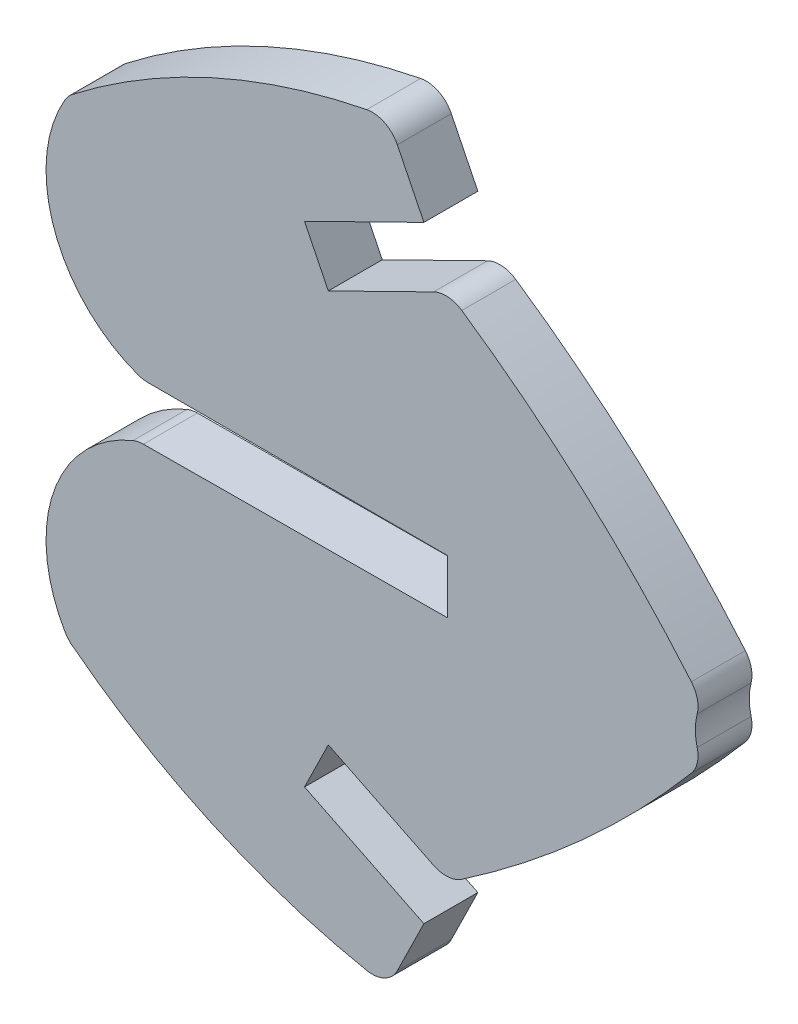
SolidWorks part; units mm, degrees
ref_plane "Front Plane" through (0, 0, 0) normal (0, 0, 1) x (1, 0, 0)
ref_plane "Top Plane" through (0, 0, 0) normal (0, 1, 0) x (1, 0, 0)
ref_plane "Right Plane" through (0, 0, 0) normal (1, 0, 0) x (0, 0, -1)
sketch "Sketch1" plane through (0, 0, 0) normal (0, 0, 1) x (1, 0, 0)
  line L0 (73.3998, -0.762) -> (76.0728, -0.762) construction
  line L2 (73.0006, 6.2526) -> (70.0273, 4.7907)
  line L3 (70.0273, 4.7907) -> (69.3549, 6.1583)
  line L4 (69.3549, 6.1583) -> (72.7273, 7.8165)
  line L5 (72.7273, 7.8165) -> (71.978, 9.3405)
  line L6 (72.7273, -9.3405) -> (71.978, -10.8645)
  line L7 (73.3998, -1.524) -> (73.3998, 0)
  line L8 (73.3998, 0) -> (64.9298, 0)
  line L9 (69.3549, -7.6823) -> (72.7273, -9.3405)
  line L10 (70.0273, -6.3147) -> (69.3549, -7.6823)
  line L11 (73.0006, -7.7766) -> (70.0273, -6.3147)
  line L12 (73.3998, -1.524) -> (64.8049, -1.5704)
  arc A0 (73.7975, 6.1965) -> (80.2836, 0.3557) centre (55.6042, -20.5286) cw
  arc A1 (71.1116, 9.769) -> (62.7883, 5.9761) centre (74.9682, -9.7236) ccw
  arc A2 (71.978, 9.3405) -> (71.1116, 9.769) centre (71.2657, 8.9903) ccw
  arc A3 (62.5889, 5.7485) -> (64.6603, 0.0471) centre (66.0008, 3.7611) ccw
  arc A4 (73.0006, 6.2526) -> (73.7975, 6.1965) centre (73.3509, 5.5403) cw
  arc A5 (62.5889, 5.7485) -> (62.7883, 5.9761) centre (63.2748, 5.349) cw
  arc A6 (64.6603, 0.0471) -> (64.9298, 0) centre (64.9298, 0.7938) ccw
  arc A7 (62.5889, -7.2725) -> (62.7883, -7.5001) centre (63.2748, -6.873) ccw
  arc A8 (73.0006, -7.7766) -> (73.7975, -7.7205) centre (73.3509, -7.0643) ccw
  arc A9 (62.5889, -7.2725) -> (64.5093, -1.6292) centre (66.0008, -5.2851) cw
  arc A10 (71.978, -10.8645) -> (71.1116, -11.293) centre (71.2657, -10.5143) cw
  arc A11 (71.1116, -11.293) -> (62.7883, -7.5001) centre (74.9682, 8.1996) cw
  arc A12 (73.7975, -7.7205) -> (80.2836, -1.8797) centre (55.6042, 19.0046) ccw
  arc A13 (64.5093, -1.6292) -> (64.8049, -1.5704) centre (64.8091, -2.3641) cw
  arc A14 (80.447, -1.1718) -> (80.447, -0.3522) centre (82.0624, -0.762) cw
  arc A15 (80.2836, -1.8797) -> (80.447, -1.1718) centre (79.6776, -1.367) ccw
  arc A16 (80.2836, 0.3557) -> (80.447, -0.3522) centre (79.6776, -0.157) cw
  point P48 (64.6603, -1.5711)
  point P49 (80.5803, -1.524)
  point P52 (80.5803, 0)
  dimension "D1" = 0.7937
  dimension "D2" = 0.7937
  dimension "D3" = 0.7937
  dimension "D4" = 0.7937
  dimension "D5" = 0.7937
extrude "Boss-Extrude1" add sketch "Sketch1" along normal blind 1.524
